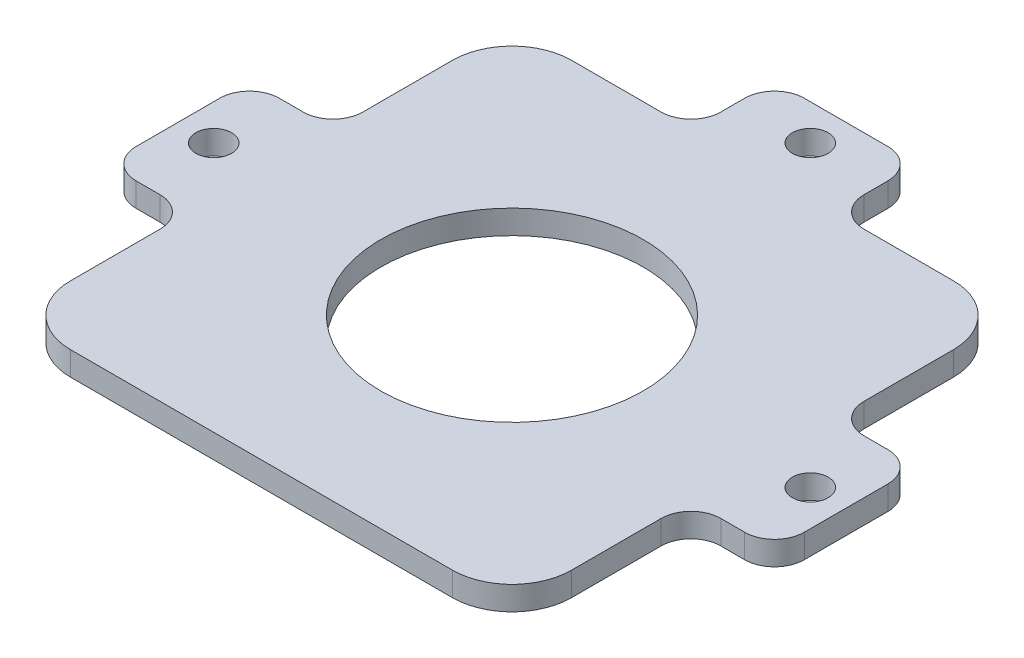
SolidWorks part; units mm, degrees
material "AISI 304"
ref_plane "Front Plane" through (0, 0, 0) normal (0, 0, 1) x (1, 0, 0)
ref_plane "Top Plane" through (0, 0, 0) normal (0, 1, 0) x (1, 0, 0)
ref_plane "Right Plane" through (0, 0, 0) normal (1, 0, 0) x (0, 0, -1)
sketch "Sketch1" plane through (0, 0, 0) normal (0, 1, 0) x (1, 0, 0)
  line L0 (0, 0) -> (0, 33.6449) construction
  line L5 (0, 0) -> (35.5051, 0) construction
  line L64 (0, 0) -> (-28.6023, 0) construction
  line L66 (21, 6) -> (28, 6)
  line L68 (21, -6) -> (28, -6)
  line L69 (28, 6) -> (28, -6)
  line L70 (21, 21) -> (6, 21)
  line L71 (21, 21) -> (21, 6)
  line L73 (-21, 21) -> (-21, 6)
  line L81 (0, 0) -> (-25, 0) construction
  line L88 (-28, -6) -> (-28, 6)
  line L89 (0, 0) -> (0, 25) construction
  line L90 (-21, -21) -> (21, -21)
  line L91 (-21, -6) -> (-28, -6)
  line L92 (-21, 6) -> (-28, 6)
  line L97 (-6, 28) -> (6, 28)
  line L100 (-6, 21) -> (-6, 28)
  line L101 (6, 21) -> (6, 28)
  line L103 (-6, 21) -> (-21, 21)
  line L104 (-21, -6) -> (-21, -21)
  line L105 (21, -6) -> (21, -21)
  line L112 (-6, -21) -> (-6, -28) [skipped]
  line L113 (6, -21) -> (6, -28) [skipped]
  line L114 (6, -28) -> (-6, -28) [skipped]
  circle A5 centre (0, 0) radius 11
  circle A9 centre (-25, 0) radius 1.5
  circle A10 centre (0, 25) radius 1.5
  circle A11 centre (25, 0) radius 1.5
  point P0 (0, 0)
  point P6 (-23.85, 0)
  point P8 (0, 0)
  point P9 (0, 0)
  point P10 (0, 0)
  point P24 (0, -23.85)
  point P25 (0, 0)
  point P55 (0, 0)
  point P66 (0, 0)
  point P84 (0, 0)
  dimension "D1" = 42
  dimension "D2" = 3
  dimension "D8" = 12
  dimension "D15" = 22
  dimension "D9" = 21
  dimension "D4" = 7
  dimension "D5" = 21
  dimension "D3" = 3
  dimension "D10" = 6
  dimension "D13" = 4
  dimension "D7" = 21
  dimension "D6" = 3
extrude "Boss-Extrude1" add sketch "Sketch1" along normal blind 2
fillet "Fillet2" radius 5 4 edges at (-21, 1, -21) (21, 1, -21) (21, 1, 21) (-21, 1, 21)
fillet "Fillet1" radius 2.5 12 edges at (-21, 1, -6) (-28, 1, -6) (-21, 1, 6) (-28, 1, 6) (6, 1, -21) (6, 1, -28) (-6, 1, -28) (-6, 1, -21) (21, 1, 6) (28, 1, 6) (28, 1, -6) (21, 1, -6)
